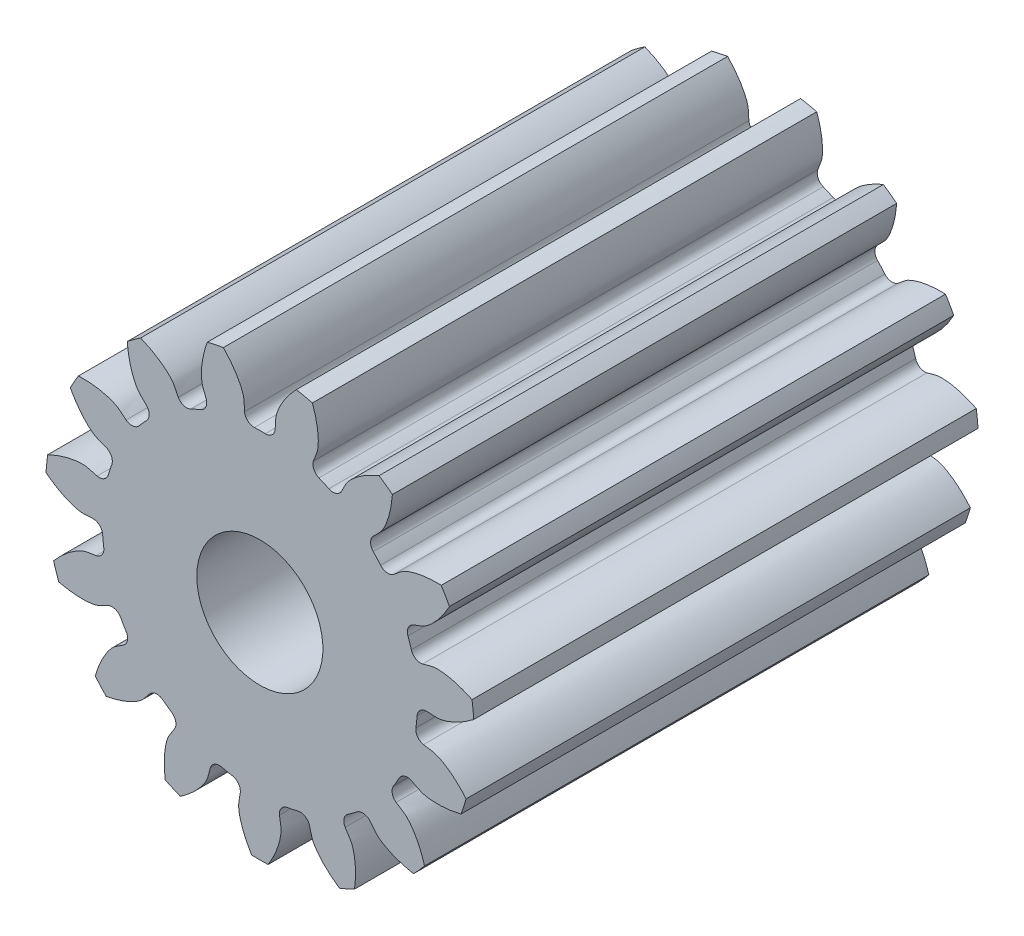
SolidWorks part; units mm, degrees
ref_plane "Front" through (0, 0, 0) normal (0, 0, 1) x (1, 0, 0)
ref_plane "Top" through (0, 0, 0) normal (0, 1, 0) x (1, 0, 0)
ref_plane "Right" through (0, 0, 0) normal (1, 0, 0) x (0, 0, -1)
ref_axis "Axis1" through (0, 0, -80.9) along (0, 0, 1)
sketch "草图1" plane through (0, 0, 0) normal (0, 0, 1) x (1, 0, 0)
  circle A0 centre (0, 0) radius 8.5
extrude "LaShenA" add sketch "草图1" along normal blind 20
sketch "SketchA" plane through (0, 0, 20) normal (0, 0, 1) x (1, 0, 0)
  line L0 (0, 0) -> (0, 8.5) construction
  arc A0 (0.2158, 6.2463) -> (-0.2158, 6.2463) centre (0, 0) ccw
  arc A1 (1.9362, 8.8239) -> (-1.9362, 8.8239) centre (0, 0) ccw
  arc A2 (-0.2158, 6.2463) -> (-0.6073, 6.5905) centre (-0.229, 6.626) cw
  arc A3 (0.6073, 6.5905) -> (0.2158, 6.2463) centre (0.229, 6.626) cw
  circle A4 centre (0, 0) radius 7.0477 construction
  circle A5 centre (0, 0) radius 8.5 construction
  circle A6 centre (0, 0) radius 6.25 construction
  circle A7 centre (0, 0) radius 7.5 construction
  spline S0 degree 3 poles (0.6073, 6.5905) (0.6208, 6.7338) (0.611, 6.9037) (0.6441, 7.0815) (0.6571, 7.1306) (0.6684, 7.1694) (0.6828, 7.2137) (0.7005, 7.2635) (0.7221, 7.3185) (0.7476, 7.3786) (0.7776, 7.4435) (0.8122, 7.5131) (0.8518, 7.5871) (0.8967, 7.6652) (0.9472, 7.7474) (1.0034, 7.8331) (1.0658, 7.9223) (1.1344, 8.0146) (1.2097, 8.1096) (1.2917, 8.2072) (1.3808, 8.3069) (1.477, 8.4084) (1.5806, 8.5115) (1.7318, 8.6532) (1.8524, 8.7562) (1.9362, 8.8239) knots 0.123008 0.123008 0.123008 0.123008 0.262739 0.288009 0.299133 0.312281 0.327451 0.344644 0.36386 0.385098 0.408359 0.433643 0.46095 0.490279 0.521631 0.555005 0.590403 0.627823 0.667265 0.708731 0.752219 0.79773 0.845263 0.894819 1 1 1 1
  spline S1 degree 3 poles (-0.6073, 6.5905) (-0.6208, 6.7338) (-0.611, 6.9037) (-0.6441, 7.0815) (-0.6571, 7.1306) (-0.6684, 7.1694) (-0.6828, 7.2137) (-0.7005, 7.2635) (-0.7221, 7.3185) (-0.7476, 7.3786) (-0.7776, 7.4435) (-0.8122, 7.5131) (-0.8518, 7.5871) (-0.8967, 7.6652) (-0.9472, 7.7474) (-1.0034, 7.8331) (-1.0658, 7.9223) (-1.1344, 8.0146) (-1.2097, 8.1096) (-1.2917, 8.2072) (-1.3808, 8.3069) (-1.477, 8.4084) (-1.5806, 8.5115) (-1.7318, 8.6532) (-1.8524, 8.7562) (-1.9362, 8.8239) knots 0.123008 0.123008 0.123008 0.123008 0.262739 0.288009 0.299133 0.312281 0.327451 0.344644 0.36386 0.385098 0.408359 0.433643 0.46095 0.490279 0.521631 0.555005 0.590403 0.627823 0.667265 0.708731 0.752219 0.79773 0.845263 0.894819 1 1 1 1
  dimension "D1" = 0.38
  dimension "Db" = 14.0954
  dimension "Da" = 17
  dimension "Df" = 12.5
  dimension "Dn" = 15
extrude "Cut-ExtrudeA" cut sketch "SketchA" against normal blind 30
pattern_circular "阵列(圆周)1" count 15 over 360 about axis through (0, 0, -80.9) along (0, 0, 1) of "Cut-ExtrudeA"
sketch "草图3" plane through (0, 0, 0) normal (0, 0, -1) x (-1, 0, 0)
  circle A0 centre (0, 0) radius 2.5
extrude "切除-拉伸2" cut sketch "草图3" against normal through all
